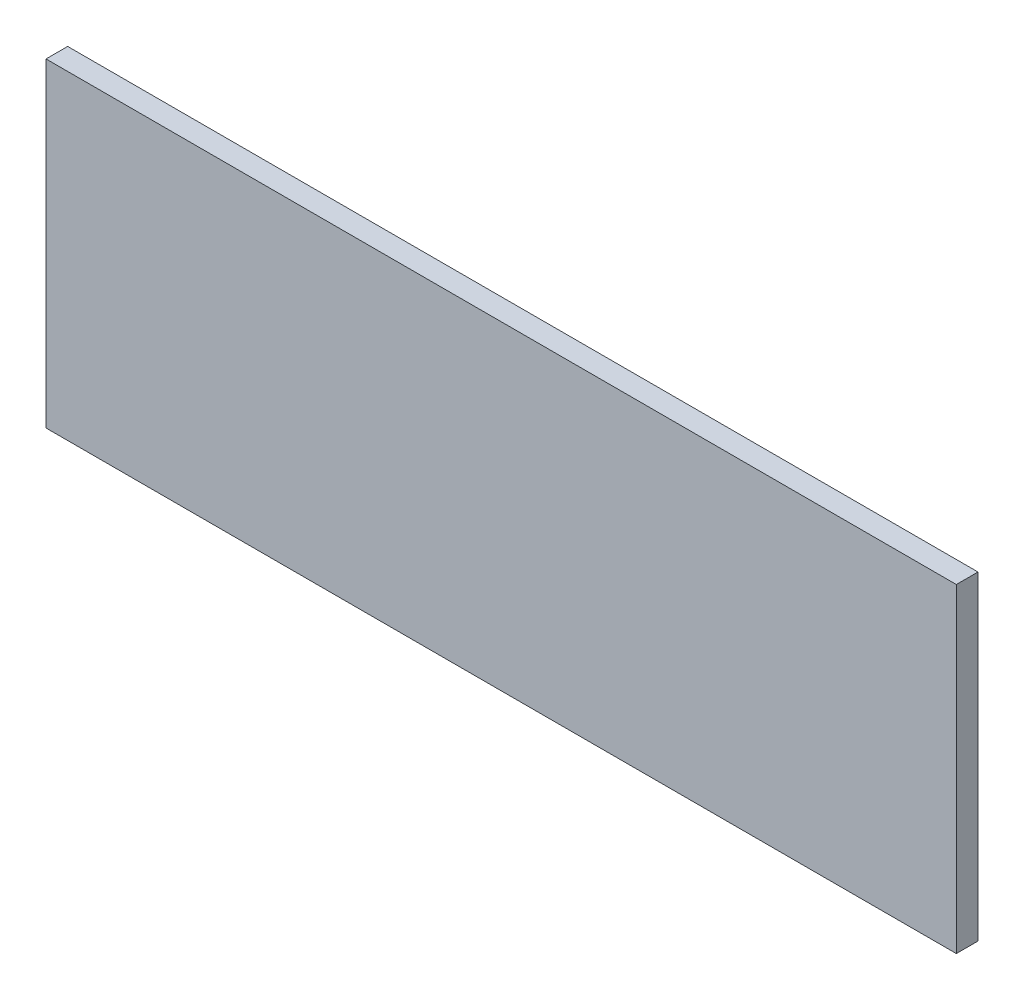
SolidWorks part; units mm, degrees
ref_plane "Front Plane" through (0, 0, 0) normal (0, 0, 1) x (1, 0, 0)
ref_plane "Top Plane" through (0, 0, 0) normal (0, 1, 0) x (1, 0, 0)
ref_plane "Right Plane" through (0, 0, 0) normal (1, 0, 0) x (0, 0, -1)
sketch "Sketch1" plane through (0, 0, 0) normal (0, 0, 1) x (1, 0, 0)
  line L1 (-41.9751, 22.4157) -> (24.6999, 22.4157)
  line L2 (-41.9751, 22.4157) -> (-41.9751, -0.9955)
  line L3 (-41.9751, -0.9955) -> (24.6999, -0.9955)
  line L4 (24.6999, 22.4157) -> (24.6999, -0.9955)
  dimension "D1" = 66.675
  dimension "D2" = 23.4112
extrude "Boss-Extrude1" add sketch "Sketch1" along normal blind 1.5875
